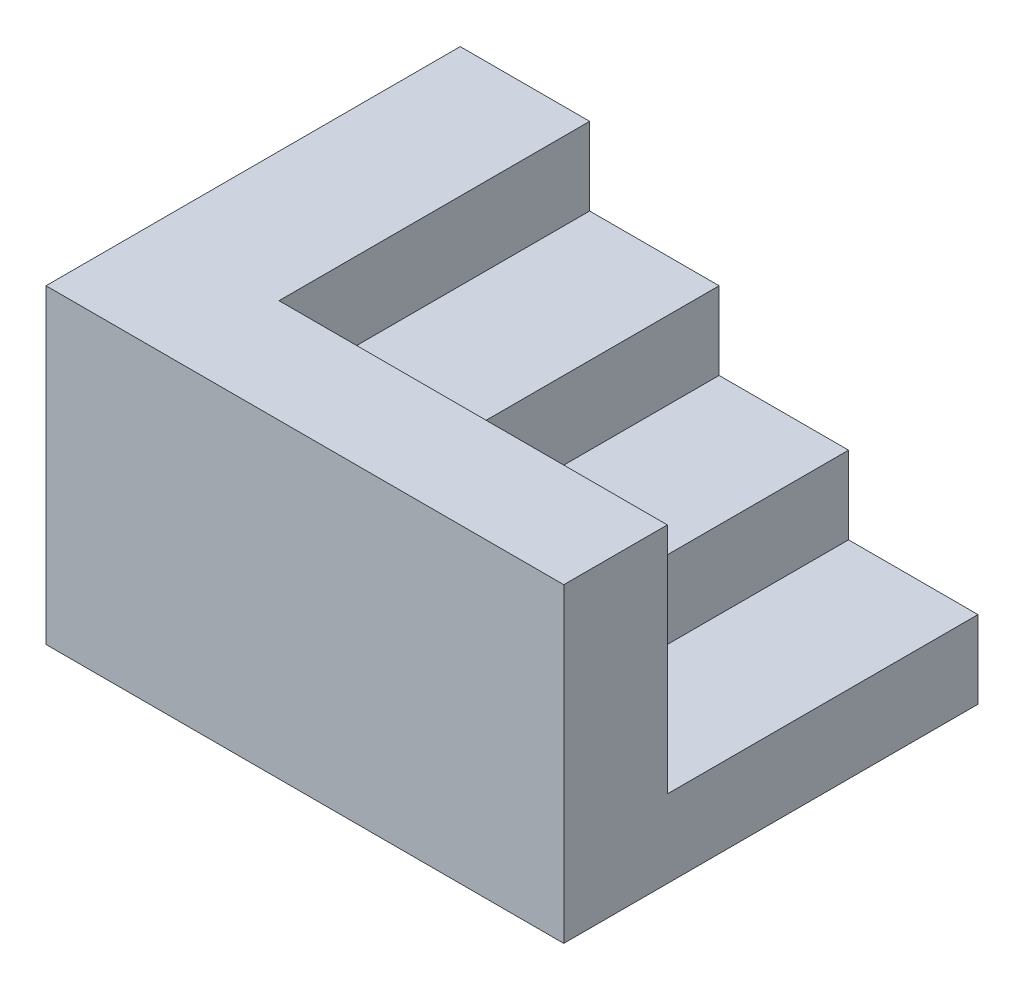
SolidWorks part; units mm, degrees
ref_plane "Front Plane" through (0, 0, 0) normal (0, 0, 1) x (1, 0, 0)
ref_plane "Top Plane" through (0, 0, 0) normal (0, 1, 0) x (1, 0, 0)
ref_plane "Right Plane" through (0, 0, 0) normal (1, 0, 0) x (0, 0, -1)
sketch "Sketch1" plane through (0, 0, 0) normal (0, 0, 1) x (1, 0, 0)
  line L1 (-50, 30) -> (50, 30)
  line L2 (-50, 30) -> (-50, -30)
  line L3 (-50, -30) -> (50, -30)
  line L4 (50, 30) -> (50, -30)
  point P7 (-99.4638, 40.6836)
  dimension "D1" = 100
  dimension "D2" = 60
  dimension "D3" = 50
  dimension "D4" = 30
extrude "Boss-Extrude1" add sketch "Sketch1" along normal blind 80
sketch "Sketch2" plane through (0, 0, 0) normal (0, 0, -1) x (-1, 0, 0)
  line L0 (-50, -30) -> (-50, -15)
  line L1 (-50, -30) -> (-50, 30) construction
  line L2 (-50, -15) -> (-25, -15)
  line L3 (-25, -15) -> (-25, 0)
  line L4 (-25, 0) -> (0, 0)
  line L5 (0, 0) -> (0, 15)
  line L6 (0, 15) -> (25, 15)
  line L7 (25, 15) -> (25, 30)
  line L8 (-50, 30) -> (50, 30) construction
  line L9 (25, 30) -> (50, 30)
  dimension "D1" = 15
  dimension "D2" = 25
extrude "Cut-Extrude1" cut sketch "Sketch2" against normal blind 60 and the other way through all
